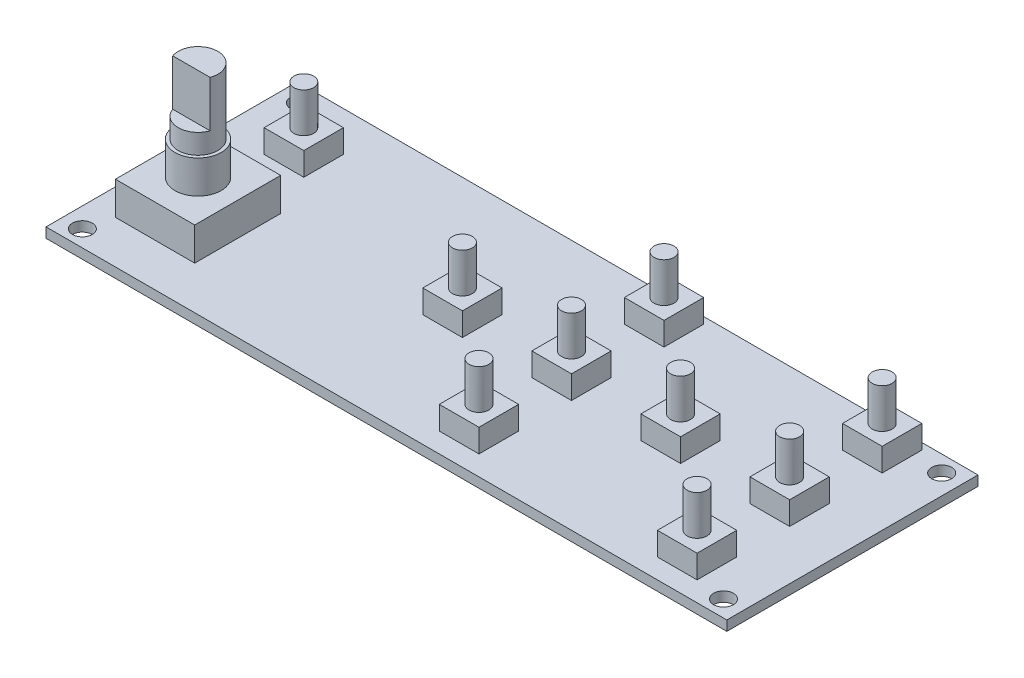
SolidWorks part; units mm, degrees
ref_plane "Front Plane" through (0, 0, 0) normal (0, 0, 1) x (1, 0, 0)
ref_plane "Top Plane" through (0, 0, 0) normal (0, 1, 0) x (1, 0, 0)
ref_plane "Right Plane" through (0, 0, 0) normal (1, 0, 0) x (0, 0, -1)
sketch "Sketch1" plane through (0, 0, 0) normal (0, 1, 0) x (1, 0, 0)
  line L0 (-51.5, 19) -> (51.5, -19) construction
  line L1 (-51.5, 19) -> (51.5, 19)
  line L2 (-51.5, 19) -> (-51.5, -19)
  line L3 (-51.5, -19) -> (51.5, -19)
  line L4 (51.5, 19) -> (51.5, -19)
  dimension "D1" = 103
  dimension "D2" = 38
extrude "Boss-Extrude1" add sketch "Sketch1" along normal blind 1.5
sketch "Sketch2" plane through (0, 1.5, 0) normal (0, 1, 0) x (1, 0, 0)
  line L0 (48.5, 16.5) -> (-48.5, 16.5) construction
  line L1 (-48.5, 16.5) -> (-48.5, -16.5) construction
  line L2 (-48.5, -16.5) -> (48.5, -16.5) construction
  line L3 (48.5, -16.5) -> (48.5, 16.5) construction
  line L4 (48.5, 16.5) -> (-48.5, -16.5) construction
  circle A0 centre (-48.5, 16.5) radius 1.5
  circle A1 centre (-48.5, -16.5) radius 1.5
  circle A2 centre (48.5, -16.5) radius 1.5
  circle A3 centre (48.5, 16.5) radius 1.5
  dimension "D1" = 3
  dimension "D2" = 97
  dimension "D3" = 33
extrude "Cut-Extrude1" cut sketch "Sketch2" against normal through all
sketch "Sketch3" plane through (0, 1.5, 0) normal (0, 1, 0) x (1, 0, 0)
  line L0 (-8.5, 1) -> (24.5, 1) construction
  line L1 (8, 15) -> (8, -13) construction
  line L2 (24.5, 1) -> (41, 1) construction
  line L3 (41, 15) -> (41, -13) construction
  line L4 (51.5, -19) -> (51.5, 19) construction
  line L5 (51.5, 19) -> (-51.5, 19) construction
  line L6 (-51.5, 19) -> (-51.5, -19) construction
  circle A0 centre (41, 15) radius 1.5
  circle A1 centre (41, 1) radius 1.5
  circle A2 centre (41, -13) radius 1.5
  circle A3 centre (24.5, 1) radius 1.5
  circle A4 centre (8, 1) radius 1.5
  circle A5 centre (8, 15) radius 1.5
  circle A6 centre (8, -13) radius 1.5
  circle A7 centre (-8.5, 1) radius 1.5
  circle A8 centre (-41.5, 10) radius 1.5
  dimension "D1" = 3
  dimension "D5" = 16.5
  dimension "D7" = 4
  dimension "D8" = 9
  dimension "D9" = 10
  dimension "D2" = 28
  dimension "D3" = 28
  dimension "D4" = 16.5
  dimension "D6" = 10.5
extrude "Boss-Extrude2" add sketch "Sketch3" along normal blind 9.5
sketch "Sketch5" plane through (0, 1.5, 0) normal (0, 1, 0) x (1, 0, 0)
  line L1 (5, 12) -> (11, 12)
  line L2 (5, 12) -> (5, 18)
  line L3 (5, 18) -> (11, 18)
  line L4 (11, 12) -> (11, 18)
  line L5 (5, 12) -> (11, 18) construction
  line L6 (5, 18) -> (11, 12) construction
  line L7 (21.5, -2) -> (27.5, -2)
  line L8 (21.5, -2) -> (21.5, 4)
  line L9 (21.5, 4) -> (27.5, 4)
  line L10 (27.5, -2) -> (27.5, 4)
  line L11 (21.5, -2) -> (27.5, 4) construction
  line L12 (21.5, 4) -> (27.5, -2) construction
  line L13 (5, -2) -> (11, -2)
  line L14 (5, -2) -> (5, 4)
  line L15 (5, 4) -> (11, 4)
  line L16 (11, -2) -> (11, 4)
  line L17 (5, -2) -> (11, 4) construction
  line L18 (5, 4) -> (11, -2) construction
  line L19 (-11.5, -2) -> (-5.5, -2)
  line L20 (-11.5, -2) -> (-11.5, 4)
  line L21 (-11.5, 4) -> (-5.5, 4)
  line L22 (-5.5, -2) -> (-5.5, 4)
  line L23 (-11.5, -2) -> (-5.5, 4) construction
  line L24 (-11.5, 4) -> (-5.5, -2) construction
  line L25 (5, -16) -> (11, -16)
  line L26 (5, -16) -> (5, -10)
  line L27 (5, -10) -> (11, -10)
  line L28 (11, -16) -> (11, -10)
  line L29 (5, -16) -> (11, -10) construction
  line L30 (5, -10) -> (11, -16) construction
  line L31 (38, -16) -> (44, -16)
  line L32 (38, -16) -> (38, -10)
  line L33 (38, -10) -> (44, -10)
  line L34 (44, -16) -> (44, -10)
  line L35 (38, -16) -> (44, -10) construction
  line L36 (38, -10) -> (44, -16) construction
  line L37 (38, -2) -> (44, -2)
  line L38 (38, -2) -> (38, 4)
  line L39 (38, 4) -> (44, 4)
  line L40 (44, -2) -> (44, 4)
  line L41 (38, -2) -> (44, 4) construction
  line L42 (38, 4) -> (44, -2) construction
  line L43 (44, 18) -> (38, 18)
  line L44 (44, 18) -> (44, 12)
  line L45 (44, 12) -> (38, 12)
  line L46 (38, 18) -> (38, 12)
  line L47 (44, 18) -> (38, 12) construction
  line L48 (44, 12) -> (38, 18) construction
  line L49 (-44.5, 13) -> (-38.5, 13)
  line L50 (-44.5, 13) -> (-44.5, 7)
  line L51 (-44.5, 7) -> (-38.5, 7)
  line L52 (-38.5, 13) -> (-38.5, 7)
  line L53 (-44.5, 13) -> (-38.5, 7) construction
  line L54 (-44.5, 7) -> (-38.5, 13) construction
  point P0 (8, 15)
  point P6 (24.5, 1)
  point P12 (8, 1)
  point P18 (-8.5, 1)
  point P24 (8, -13)
  point P30 (41, -13)
  point P36 (41, 1)
  point P42 (41, 15)
  point P48 (-41.5, 10)
  dimension "D1" = 6
  dimension "D2" = 6
extrude "Boss-Extrude3" add sketch "Sketch5" along normal blind 3.5
sketch "Sketch6" plane through (0, 1.5, 0) normal (0, 1, 0) x (1, 0, 0)
  line L0 (-51.5, -19) -> (51.5, -19) construction
  line L1 (-38.6716, -7) -> (-44.3284, -7)
  line L2 (-51.5, 19) -> (-51.5, -19) construction
  arc A0 (-38.6716, -7) -> (-44.3284, -7) centre (-41.5, -6) ccw
  dimension "D1" = 3
  dimension "D3" = 13
  dimension "D4" = 10
  dimension "D2" = 1
extrude "Boss-Extrude4" add sketch "Sketch6" along normal blind 20
sketch "Sketch7" plane through (0, 1.5, 0) normal (0, 1, 0) x (1, 0, 0)
  circle A0 centre (-41.5, -6) radius 3
  arc A1 (-38.6716, -7) -> (-44.3284, -7) centre (-41.5, -6) ccw construction
extrude "Boss-Extrude5" add sketch "Sketch7" along normal blind 13
sketch "Sketch8" plane through (0, 1.5, 0) normal (0, 1, 0) x (1, 0, 0)
  circle A0 centre (-41.5, -6) radius 3.5
  dimension "D1" = 7
extrude "Boss-Extrude6" add sketch "Sketch8" along normal blind 10
sketch "Sketch9" plane through (0, 1.5, 0) normal (0, 1, 0) x (1, 0, 0)
  line L1 (-47.5, -12.5) -> (-35.5, -12.5)
  line L2 (-47.5, -12.5) -> (-47.5, 0.5)
  line L3 (-47.5, 0.5) -> (-35.5, 0.5)
  line L4 (-35.5, -12.5) -> (-35.5, 0.5)
  line L5 (-47.5, -12.5) -> (-35.5, 0.5) construction
  line L6 (-47.5, 0.5) -> (-35.5, -12.5) construction
  point P0 (-41.5, -6)
  dimension "D1" = 12
  dimension "D2" = 13
extrude "Boss-Extrude7" add sketch "Sketch9" along normal blind 5
